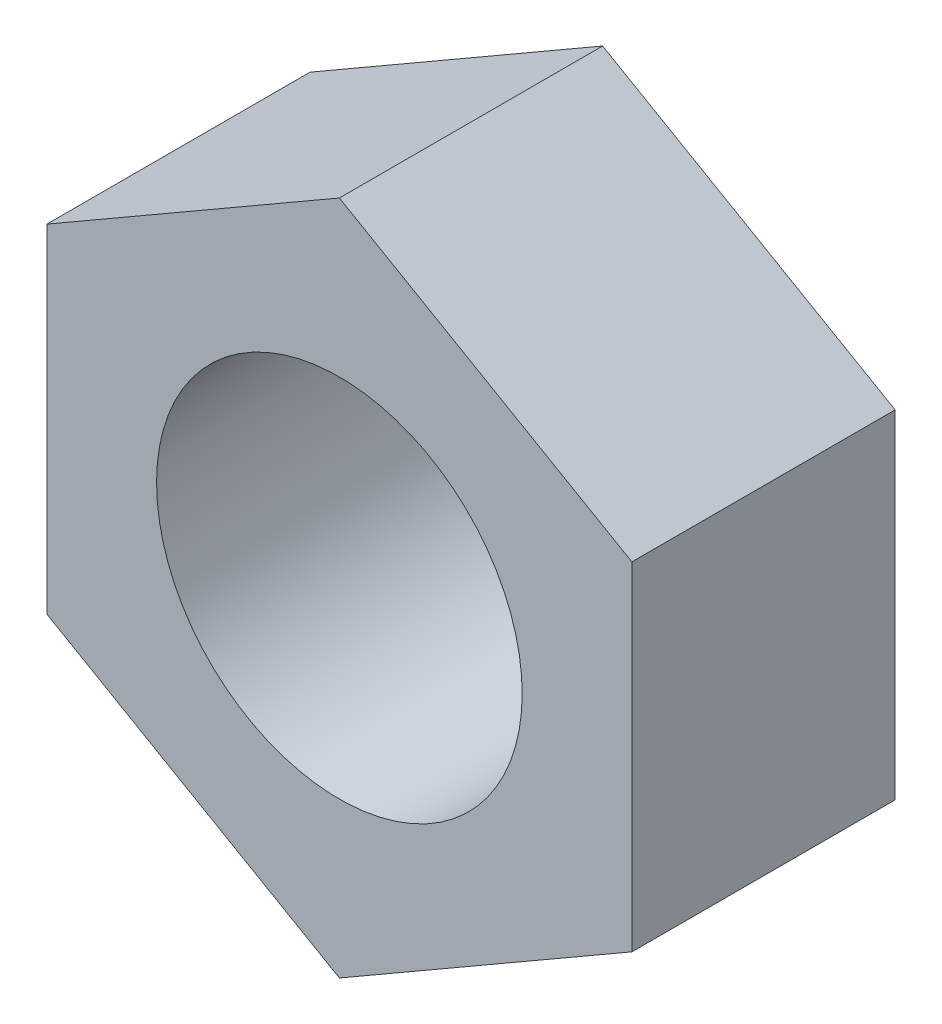
SolidWorks part; units mm, degrees
ref_plane "Спереди" through (0, 0, 0) normal (0, 0, 1) x (1, 0, 0)
ref_plane "Сверху" through (0, 0, 0) normal (0, 1, 0) x (1, 0, 0)
ref_plane "Справа" through (0, 0, 0) normal (1, 0, 0) x (0, 0, -1)
sketch "Эскиз1" plane through (0, 0, 0) normal (0, 0, 1) x (1, 0, 0)
  line L1 (0, 4.6188) -> (-4, 2.3094)
  line L2 (-4, 2.3094) -> (-4, -2.3094)
  line L3 (-4, -2.3094) -> (0, -4.6188)
  line L4 (0, -4.6188) -> (4, -2.3094)
  line L5 (4, -2.3094) -> (4, 2.3094)
  line L6 (4, 2.3094) -> (0, 4.6188)
  circle A0 centre (0, 0) radius 4 construction
  circle A1 centre (0, 0) radius 2.5
  dimension "D2" = 5
  dimension "D1" = 8
extrude "Вытянуть1" add sketch "Эскиз1" along normal blind 3.6
